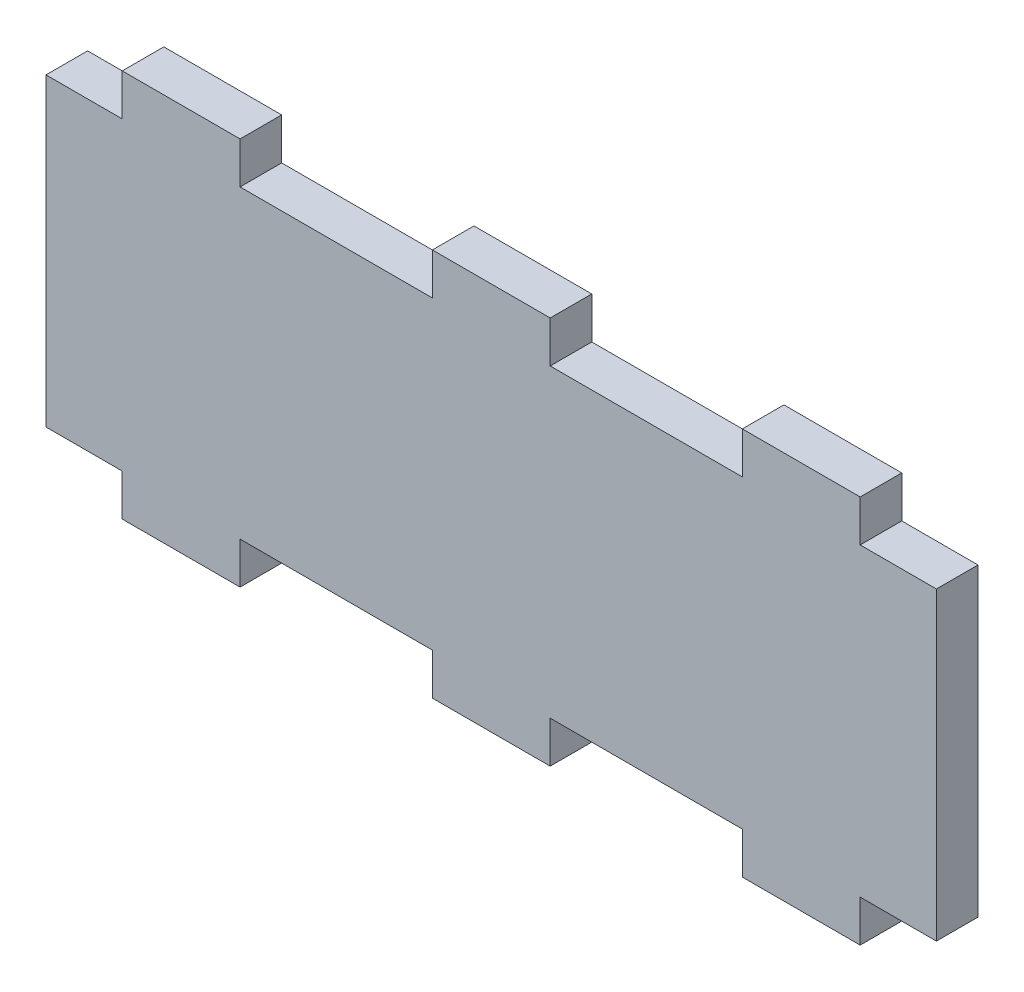
SolidWorks part; units mm, degrees
material "Balsa"
ref_plane "Alzado" through (0, 0, 0) normal (0, 0, 1) x (1, 0, 0)
ref_plane "Planta" through (0, 0, 0) normal (0, 1, 0) x (1, 0, 0)
ref_plane "Vista lateral" through (0, 0, 0) normal (1, 0, 0) x (0, 0, -1)
sketch "Croquis1" plane through (0, 0, 0) normal (0, 0, 1) x (1, 0, 0)
  line L0 (17, 0) -> (30.87, 0)
  line L1 (3, 0) -> (8.5, 0)
  line L3 (3, 22) -> (8.5, 22)
  line L6 (8.5, 0) -> (8.5, -3)
  line L7 (8.5, -3) -> (17, -3)
  line L8 (17, 0) -> (17, -3)
  line L10 (30.87, 0) -> (30.87, -3)
  line L11 (30.87, -3) -> (39.37, -3)
  line L12 (39.37, 0) -> (39.37, -3)
  line L14 (53.23, 0) -> (53.23, -3)
  line L15 (53.23, -3) -> (61.73, -3)
  line L16 (61.73, 0) -> (61.73, -3)
  line L17 (39.37, 0) -> (53.23, 0)
  line L18 (61.73, 0) -> (67.23, 0)
  line L19 (3, 11) -> (67.23, 11) construction
  line L20 (61.73, 22) -> (61.73, 25)
  line L21 (53.23, 22) -> (53.23, 25)
  line L22 (39.37, 22) -> (39.37, 25)
  line L23 (30.87, 22) -> (30.87, 25)
  line L24 (17, 22) -> (17, 25)
  line L25 (8.5, 22) -> (8.5, 25)
  line L26 (53.23, 25) -> (61.73, 25)
  line L27 (30.87, 25) -> (39.37, 25)
  line L28 (8.5, 25) -> (17, 25)
  line L29 (17, 22) -> (30.87, 22)
  line L30 (39.37, 22) -> (53.23, 22)
  line L31 (61.73, 22) -> (67.23, 22)
  line L32 (3, 22) -> (3, 0)
  line L33 (67.23, 22) -> (67.23, 0)
  dimension "D3" = 3
  dimension "D4" = 8.5
  dimension "D5" = 8.5
  dimension "D6" = 8.5
  dimension "D8" = 13.87
extrude "Saliente-Extruir1" add sketch "Croquis1" along normal blind 3
